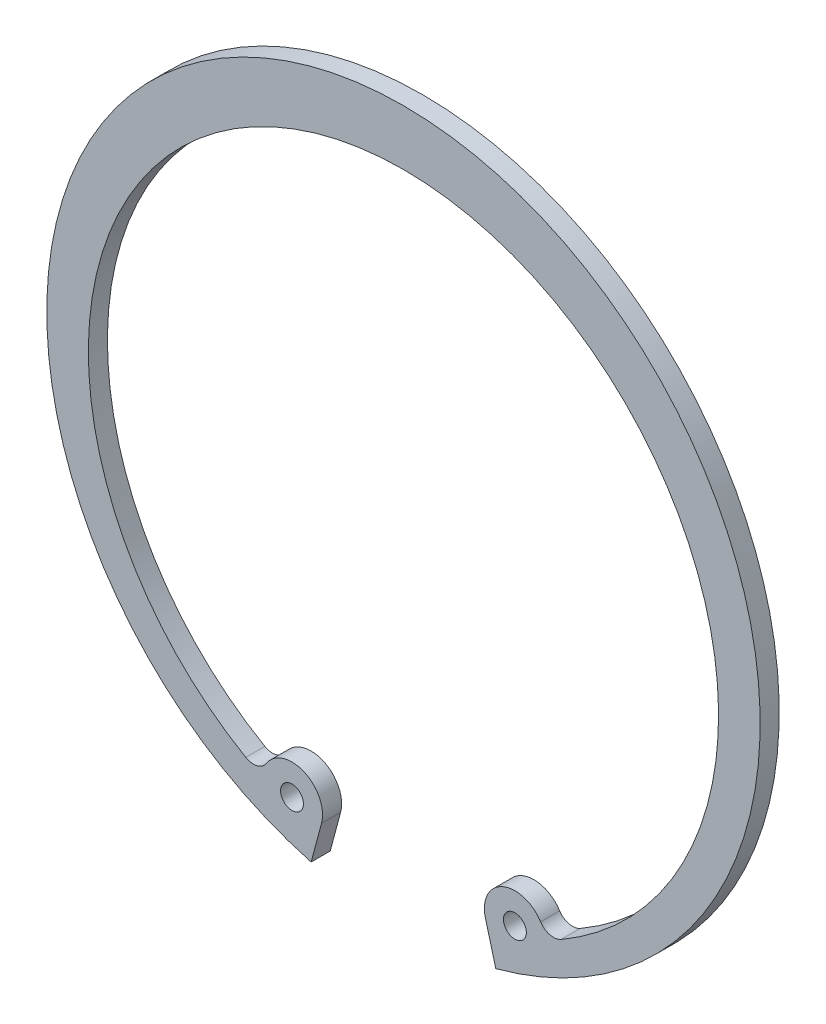
SolidWorks part; units mm, degrees
ref_plane "Front" through (0, 0, 0) normal (0, 0, 1) x (1, 0, 0)
ref_plane "Top" through (0, 0, 0) normal (0, 1, 0) x (1, 0, 0)
ref_plane "Right" through (0, 0, 0) normal (1, 0, 0) x (0, 0, -1)
sketch "Sketch1" plane through (0, 0, 0) normal (0, 0, 1) x (1, 0, 0)
  line L0 (0, 0) -> (-10.743, -40.0934) construction
  line L1 (0, 7.3554) -> (0, -7.1505) construction
  line L2 (10.743, -40.0934) -> (12.0998, -45.157)
  line L4 (-10.743, -40.0934) -> (-12.0998, -45.157)
  arc A0 (12.0998, -45.157) -> (-12.0998, -45.157) centre (0, 0) ccw
  arc A1 (20.6633, -37.5591) -> (-20.6633, -37.5591) centre (0, -1.8) ccw
  arc A2 (-10.743, -40.0934) -> (-17.9774, -36.9043) centre (-14.6067, -39.0581) ccw
  arc A3 (-20.6633, -37.5591) -> (-17.9774, -36.9043) centre (-19.6627, -35.8275) ccw
  circle A4 centre (14.6067, -39.0581) radius 1.5
  arc A5 (20.6633, -37.5591) -> (17.9774, -36.9043) centre (19.6627, -35.8275) cw
  arc A6 (-41.7, 0) -> (41.7, 0) centre (0, 0) ccw construction
  circle A7 centre (-14.6067, -39.0581) radius 1.5
  arc A8 (10.743, -40.0934) -> (17.9774, -36.9043) centre (14.6067, -39.0581) cw
  dimension "D" = 93.5
  dimension "d0" = 82.6
  dimension "R1" = 4
  dimension "R2" = 2
  dimension "d1" = 3
  dimension "R" = 41.7
  dimension "C" = 1.8
  dimension "Angle" = 30
extrude "Body" add sketch "Sketch1" against normal blind 2.5
